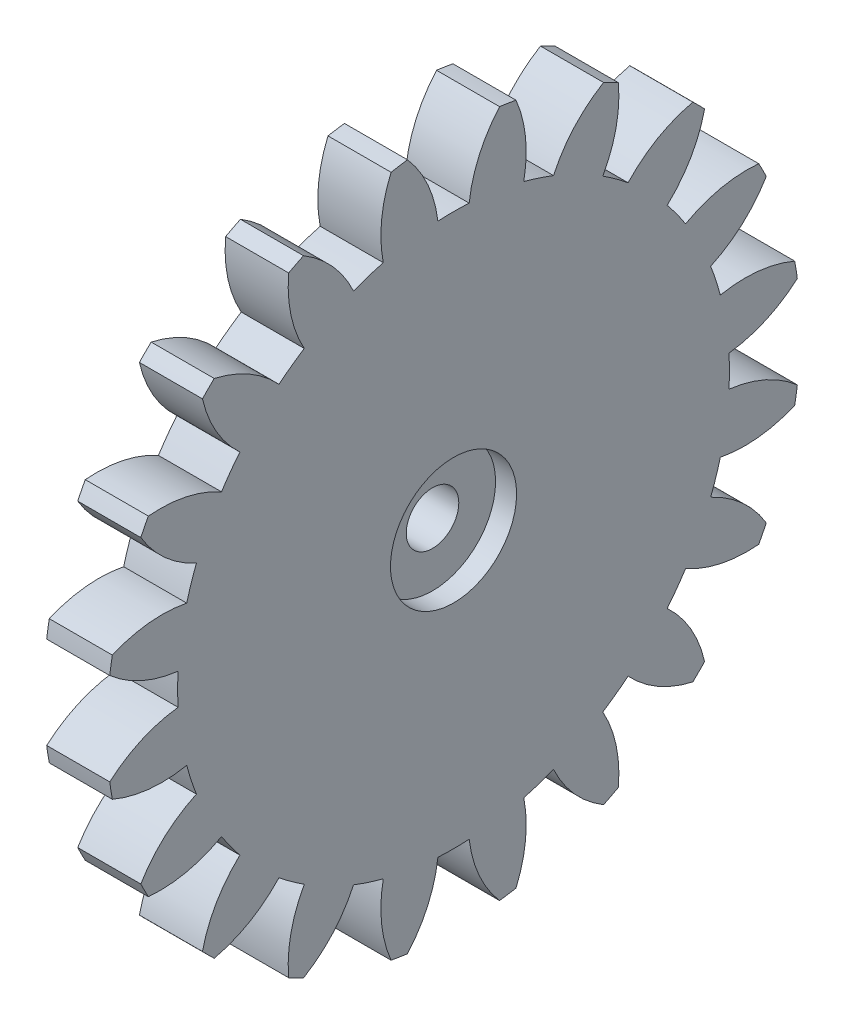
SolidWorks part; units mm, degrees
ref_plane "Plane1" through (0, 0, 0) normal (0, 0, 1) x (1, 0, 0)
ref_plane "Plane2" through (0, 0, 0) normal (0, 1, 0) x (1, 0, 0)
ref_plane "Plane3" through (0, 0, 0) normal (1, 0, 0) x (0, 0, -1)
sketch "HoldingSke" plane through (0, 0, 0) normal (0, 1, 0) x (1, 0, 0)
  line L0 (0, 0) -> (0.6265, -0.228)
  line L1 (-15, 0) -> (100, 0) construction
  line L2 (0, 0) -> (-2.1039, 2.3779)
  line L3 (0, 0) -> (-11.863, 4.5341)
  line L4 (0, 0) -> (8.1152, 2.9537)
  line L5 (0, 0) -> (-46.8476, -17.4728)
  line L6 (0, 0) -> (-2.4869, -1.6779)
  line L7 (-2.1039, 2.3779) -> (8.6586, 51.2059)
  line L8 (-76.2, 54.61) -> (-76.1, 54.61)
  line L9 (-71.009, 38.7566) -> (-53.1078, 45.2721)
  line L10 (-76.2, 71.12) -> (104.1128, 71.12)
  line L11 (0, 0) -> (-3, 0)
  line L12 (-76.2, 101.6) -> (-76.147, 101.6)
  line L13 (24.9733, 27.94) -> (52.9518, 28.4284)
  line L14 (24.9733, 27.94) -> (24.9743, 27.94)
  line L15 (24.9733, 27.94) -> (100.4006, 29.5858)
  line L16 (-63.627, -1.5) -> (-12.827, -1.5)
  circle A0 centre (0, 0) radius 0.5
  circle A1 centre (0, 0) radius 13.124
  circle A2 centre (0, 0) radius 37.5
  circle A3 centre (0, 0) radius 0.5
  dimension "MHD" = 26.248
  dimension "Hub_dia" = 75
  dimension "Bore" = 1
  dimension "MBD" = 1
  dimension "Num_teeth" = 20
  dimension "Pitch" = 0.6667
  dimension "Overall_len" = 50
  dimension "Show_teeth" = 20
  dimension "Thickness" = 3
  dimension "OAL" = 50.0001
  dimension "T_dim" = 0.1
  dimension "Ap" = 20
  dimension "H" = 19.05
  dimension "Pitch_radius" = 180.3128
  dimension "Width" = 3
  dimension "Backlash" = 0.053
  dimension "Addendum_fac" = 1
  dimension "Dedendum_fac" = 1.25
  dimension "Clearance_fac" = 0.25
  dimension "Dedendum_add" = 0.001
  dimension "Module" = 1.5
sketch "BasProSke" plane through (0, 0, 0) normal (0, 1, 0) x (1, 0, 0)
  line L0 (-10, 0) -> (60, 0) construction
  line L1 (0, 0) -> (0, 16.5)
  line L2 (0, 0) -> (3, 0)
  line L3 (3, 0) -> (3, 16.5)
  line L4 (3, 16.5) -> (0, 16.5)
  dimension "Thickness" = 3
  dimension "Diameter" = 33
revolve "Base-Revolve" add sketch "BasProSke" angle 360 about L0
sketch "TooCutSke" plane through (0, 0, 0) normal (1, 0, 0) x (0, 0, -1)
  line L1 (0, 0) -> (0, 107) construction
  line L2 (0, 0) -> (-1.2696, 14.9462) construction
  line L3 (0, 0) -> (-4.6808, 29.5532) construction
  line L4 (-1.2696, 14.9462) -> (-2.3404, 14.7766) construction
  arc A0 (0.7438, 13.1029) -> (-0.7438, 13.1029) centre (0, 0) ccw
  arc A1 (2.21, 16.377) -> (-2.21, 16.377) centre (0, 0) ccw
  circle A2 centre (0, 0) radius 15 construction
  circle A3 centre (0, 0) radius 14.0954 construction
  arc A4 (-0.7438, 13.1029) -> (-2.21, 16.377) centre (-6.7025, 12.3999) ccw
  arc A5 (2.21, 16.377) -> (0.7438, 13.1029) centre (6.7025, 12.3999) ccw
  dimension "Root_dia" = 26.248
  dimension "Overcut_dia" = 33.0508
  dimension "Pitch_dia" = 30
  dimension "Base_dia" = 28.1908
  dimension "Flank_rad" = 6
  dimension "Half_ang" = 9
  dimension "Half_CT" = 1.0841
extrude "ToothCut" cut sketch "TooCutSke" along normal through all
fillet "Breaks" [suppressed] radius 0.03
fillet "RootFillets" [suppressed] radius 0.376
pattern_circular "TeethCuts" count 20 every 18 about axis through (-10, 0, 0) along (1, 0, 0) of "ToothCut", "RootFillets", "Breaks"
sketch "HubNeaOneSke" plane through (0, 0, 0) normal (-1, 0, 0) x (0, 0, 1)
  circle A0 centre (0, 0) radius 13.124
  dimension "Diameter" = 26.248
extrude "HubNearOne" [suppressed] add sketch "HubNeaOneSke" along normal blind 47.0001
sketch "HubNeaBotSke" plane through (0, 0, 0) normal (-1, 0, 0) x (0, 0, 1)
  circle A0 centre (0, 0) radius 13.124
  dimension "Diameter" = 26.248
extrude "HubNearBoth" [suppressed] add sketch "HubNeaBotSke" along normal blind 23.5
ref_plane "FarPln" through (3, 0, 0) normal (1, 0, 0) x (0, 0, -1)
sketch "HubFarSke" plane through (3, 0, 0) normal (1, 0, 0) x (0, 0, -1)
  circle A0 centre (0, 0) radius 13.124
  dimension "Diameter" = 26.248
extrude "HubFar" [suppressed] add sketch "HubFarSke" along normal blind 23.5
sketch "BorSke" plane through (0, 0, 0) normal (1, 0, 0) x (0, 0, -1)
  circle A0 centre (0, 0) radius 0.5
  dimension "Diameter" = 1
extrude "Bore" cut sketch "BorSke" along normal mid plane 100.0001
sketch "KeySke" plane through (0, 0, 0) normal (1, 0, 0) x (0, 0, -1)
  line L0 (-0.05, 0) -> (-0.05, 0.6)
  line L1 (-0.05, 0.6) -> (0.05, 0.6)
  line L2 (0.05, 0.6) -> (0.05, 0)
  line L3 (0, 0) -> (0, 34) construction
  line L4 (-0.05, 0) -> (0.05, 0)
  dimension "Offset" = 0.6
  dimension "Width" = 0.1
extrude "Keyway" [suppressed] cut sketch "KeySke" along normal mid plane 100.0001
pattern_circular "Keyway2" [suppressed] count 2 every 90 about axis through (-10, 0, 0) along (1, 0, 0)
sketch "Sketch1" plane through (0, 0, 0) normal (-1, 0, 0) x (0, 0, 1)
  line L0 (-2.0094, 1.95) -> (2.0094, 1.95)
  line L1 (-1.9666, 1.85) -> (1.9666, 1.85) construction
  line L3 (-1.9666, -1.85) -> (1.9666, -1.85) construction
  line L5 (0, -1.85) -> (0, 1.85) construction
  line L6 (-3.997, 0) -> (3.997, 0) construction
  line L7 (-2.0094, -1.95) -> (2.0094, -1.95)
  arc A0 (-1.9666, 1.85) -> (-1.9666, -1.85) centre (0, 0) ccw construction
  arc A1 (1.9666, -1.85) -> (1.9666, 1.85) centre (0, 0) ccw construction
  arc A2 (2.0094, -1.95) -> (2.0094, 1.95) centre (0, 0) ccw
  arc A3 (-2.0094, 1.95) -> (-2.0094, -1.95) centre (0, 0) ccw
  circle A4 centre (0, 0) radius 4.8
  point P0 (0, 0)
  point P1 (0, 0)
  point P189 (0, 0)
  dimension "D1" = 5.4
  dimension "D4" = 2
  dimension "D2" = 3.7
  dimension "D3" = 0.1
extrude "Boss-Extrude1" add sketch "Sketch1" along normal blind 3.88
sketch "Sketch2" plane through (3, 0, 0) normal (1, 0, 0) x (0, 0, -1)
  circle A0 centre (0, 0) radius 1.25
  dimension "D1" = 2.5
extrude "Cut-Extrude1" cut sketch "Sketch2" against normal up to next
sketch "Sketch3" plane through (3, 0, 0) normal (1, 0, 0) x (0, 0, -1)
  circle A0 centre (0, 0) radius 1.25
  circle A1 centre (0, 0) radius 3
extrude "Cut-Extrude2" cut sketch "Sketch3" against normal blind 1
equation "' \"Module@HoldingSke\" = 6.35"
equation "' \"Num_teeth@HoldingSke\" = 12"
equation "' \"Ap@HoldingSke\" =  20"
equation "' \"Ap@HoldingSke\" = 20"
equation "' \"Width@HoldingSke\" = 0.5 * 25.4"
equation "' \"Hub_dia@HoldingSke\"= 1 * 25.4"
equation "' \"Hub_dia@HoldingSke\" = 1 * 25.4"
equation "' \"Overall_len@HoldingSke\" = 1.0 * 25.4"
equation "' \"Bore@HoldingSke\" = 0.75 * 25.4"
equation "' \"T_dim@HoldingSke\" = 0.1 * 25.4"
equation "' \"Width@KeySke\" = 0.25 * 25.4"
equation "' \"Show_teeth@HoldingSke\" = 13"
equation "' \"Backlash@HoldingSke\" = 0.009 * 25.4"
equation "' \"Addendum_fac@HoldingSke\" = 1.0"
equation "' \"Dedendum_fac@HoldingSke\" = 1.25"
equation "' \"Dedendum_add@HoldingSke\" = 0.00005 * 25.4"
equation "' \"Clearance_fac@HoldingSke\" = 0.25"
equation "\"Pitch@HoldingSke\" = 1 / \"Module@HoldingSke\""
equation "\"Overcut_dia@TooCutSke\" = (\"Num_teeth@HoldingSke\" + 2 * \"Addendum_fac@HoldingSke\") / \"Pitch@HoldingSke\" + 0.002 * 25.4"
equation "\"Pitch_dia@TooCutSke\" = \"Num_teeth@HoldingSke\" / \"Pitch@HoldingSke\""
equation "\"Base_dia@TooCutSke\" = \"Num_teeth@HoldingSke\" / \"Pitch@HoldingSke\" * cos((\"Ap@HoldingSke\"  * 3.14159265 / 180))"
equation "\"Root_dia@TooCutSke\" = (\"Num_teeth@HoldingSke\" + 2) / \"Pitch@HoldingSke\" - 2 * (\"Addendum_fac@HoldingSke\" + \"Dedendum_fac@HoldingSke\") / \"Pitch@HoldingSke\" - \"Dedendum_add@HoldingSke\" * 2"
equation "\"Half_ang@TooCutSke\" = 180 / \"Num_teeth@HoldingSke\""
equation "\"Half_CT@TooCutSke\" = \"Num_teeth@HoldingSke\" / \"Pitch@HoldingSke\" * sin((3.14159265 / 2 / \"Num_teeth@HoldingSke\")) / 2 - 7 * \"Backlash@HoldingSke\" / 4"
equation "\"Flank_rad@TooCutSke\" = \"Num_teeth@HoldingSke\" / \"Pitch@HoldingSke\" / 5"
equation "\"Radius@RootFillets\" = \"Clearance_fac@HoldingSke\" / \"Pitch@HoldingSke\" + \"Dedendum_add@HoldingSke\""
equation "\"Break_rad@Breaks\" = 0.02 / \"Pitch@HoldingSke\""
equation "\"Thickness@HoldingSke\" = \"Width@HoldingSke\""
equation "\"OAL@HoldingSke\" = \"Thickness@HoldingSke\""
equation "\"MHD@HoldingSke\" = (\"Num_teeth@HoldingSke\" + 2) / \"Pitch@HoldingSke\" - 2 * (\"Addendum_fac@HoldingSke\" + \"Dedendum_fac@HoldingSke\")  / \"Pitch@HoldingSke\" - \"Dedendum_add@HoldingSke\" * 2"
equation "\"MBD@HoldingSke\" = (\"Num_teeth@HoldingSke\" + 2) / \"Pitch@HoldingSke\" - 2 * (\"Addendum_fac@HoldingSke\" + \"Dedendum_fac@HoldingSke\")  / \"Pitch@HoldingSke\" - \"Dedendum_add@HoldingSke\" * 2 - 0.002 * 25.4"
equation "\"MHD@HoldingSke\" = ((sgn( \"MHD@HoldingSke\" - \"Hub_dia@HoldingSke\" )-1)*( \"MHD@HoldingSke\" - \"Hub_dia@HoldingSke\" ))/-2+ \"Hub_dia@HoldingSke\""
equation "\"MBD@HoldingSke\" = ((sgn( \"MBD@HoldingSke\" - \"Bore@HoldingSke\" )-1)*( \"MBD@HoldingSke\" - \"Bore@HoldingSke\" ))/-2+ \"Bore@HoldingSke\""
equation "\"OAL@HoldingSke\" = ((sgn( \"OAL@HoldingSke\" - \"Overall_len@HoldingSke\" )+1)*( \"OAL@HoldingSke\" - \"Overall_len@HoldingSke\" ))/2 + \"Overall_len@HoldingSke\" + 0.000002 * 25.4"
equation "\"Num_teeth@TeethCuts\" = int( \"Show_teeth@HoldingSke\" ) + 1"
equation "\"Num_teeth@TeethCuts\" = ((sgn( \"Num_teeth@TeethCuts\" - \"Num_teeth@HoldingSke\" )-1)*( \"Num_teeth@TeethCuts\" - \"Num_teeth@HoldingSke\" ))/-2+ \"Num_teeth@HoldingSke\""
equation "\"Num_teeth@TeethCuts\" = ((sgn( \"Num_teeth@TeethCuts\" - 2.0)+1)*( \"Num_teeth@TeethCuts\" - 2.0))/2 +2.0"
equation "\"Angle@TeethCuts\" = 360.0 / \"Num_teeth@HoldingSke\""
equation "\"Diameter@BasProSke\" = (\"Num_teeth@HoldingSke\" + 2 * \"Addendum_fac@HoldingSke\") / \"Pitch@HoldingSke\""
equation "\"Thickness@BasProSke\"  = \"Thickness@HoldingSke\""
equation "' \"Fillet_rad@BasProSke\" =  \"Thickness@HoldingSke\" * 0.05"
equation "' \"Fillet_rad@BasProSke\" = \"Thickness@HoldingSke\" * 0.05"
equation "\"MHD@HoldingSke\" = ((sgn( \"MHD@HoldingSke\" - \"Root_dia@TooCutSke\" )-1)*( \"MHD@HoldingSke\" - \"Root_dia@TooCutSke\" ))/-2+ \"Root_dia@TooCutSke\""
equation "\"Diameter@HubNeaOneSke\" = \"MHD@HoldingSke\""
equation "\"Length@HubNearOne\" = \"OAL@HoldingSke\" - \"Thickness@BasProSke\""
equation "\"Diameter@HubNeaBotSke\" = \"MHD@HoldingSke\""
equation "\"Length@HubNearBoth\" = ( \"OAL@HoldingSke\" - \"Thickness@BasProSke\" ) / 2.0"
equation "\"Thickness@FarPln\" = \"Thickness@BasProSke\""
equation "\"Diameter@HubFarSke\" = \"MHD@HoldingSke\""
equation "\"Length@HubFar\" = ( \"OAL@HoldingSke\" - \"Thickness@BasProSke\" ) / 2.0"
equation "\"Diameter@BorSke\" = \"MBD@HoldingSke\""
equation "\"D1@Bore\" = \"OAL@HoldingSke\" * 2.0"
equation "\"D1@Keyway\" = \"OAL@HoldingSke\" * 2.0"
equation "\"Offset@KeySke\" = \"T_dim@HoldingSke\" + \"MBD@HoldingSke\" / 2.0"
